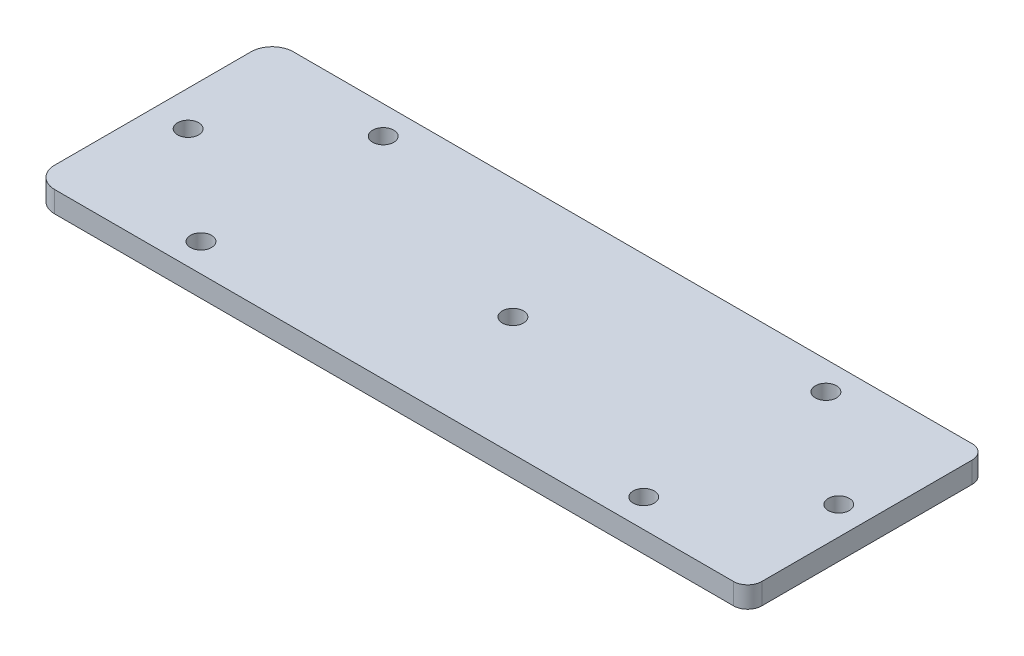
SolidWorks part; units mm, degrees
ref_plane "Front Plane" through (0, 0, 0) normal (0, 0, 1) x (1, 0, 0)
ref_plane "Top Plane" through (0, 0, 0) normal (0, 1, 0) x (1, 0, 0)
ref_plane "Right Plane" through (0, 0, 0) normal (1, 0, 0) x (0, 0, -1)
sketch "Sketch1" plane through (0, 0, 0) normal (0, 1, 0) x (1, 0, 0)
  line L0 (-56.5788, 15.2139) -> (-56.5788, -12.6361)
  line L1 (-53.5788, -15.6361) -> (42.7212, -15.6361)
  line L2 (44.7212, -13.6361) -> (44.7212, 16.2139)
  line L3 (42.7212, 18.2139) -> (-53.5788, 18.2139)
  circle A0 centre (40.7212, 1.2889) radius 1.5
  circle A1 centre (25.9712, 14.2139) radius 1.5
  circle A2 centre (-36.8288, 14.2139) radius 1.5
  circle A3 centre (-51.5788, 1.2889) radius 1.5
  circle A4 centre (-36.8288, -11.6361) radius 1.5
  circle A5 centre (-5.4288, 1.2115) radius 1.5
  circle A6 centre (25.9712, -11.6361) radius 1.5
  arc A7 (-53.5788, 18.2139) -> (-56.5788, 15.2139) centre (-53.5788, 15.2139) ccw
  arc A8 (-56.5788, -12.6361) -> (-53.5788, -15.6361) centre (-53.5788, -12.6361) ccw
  arc A9 (42.7212, -15.6361) -> (44.7212, -13.6361) centre (42.7212, -13.6361) ccw
  arc A10 (44.7212, 16.2139) -> (42.7212, 18.2139) centre (42.7212, 16.2139) ccw
extrude "Boss-Extrude1" add sketch "Sketch1" along normal blind 3
